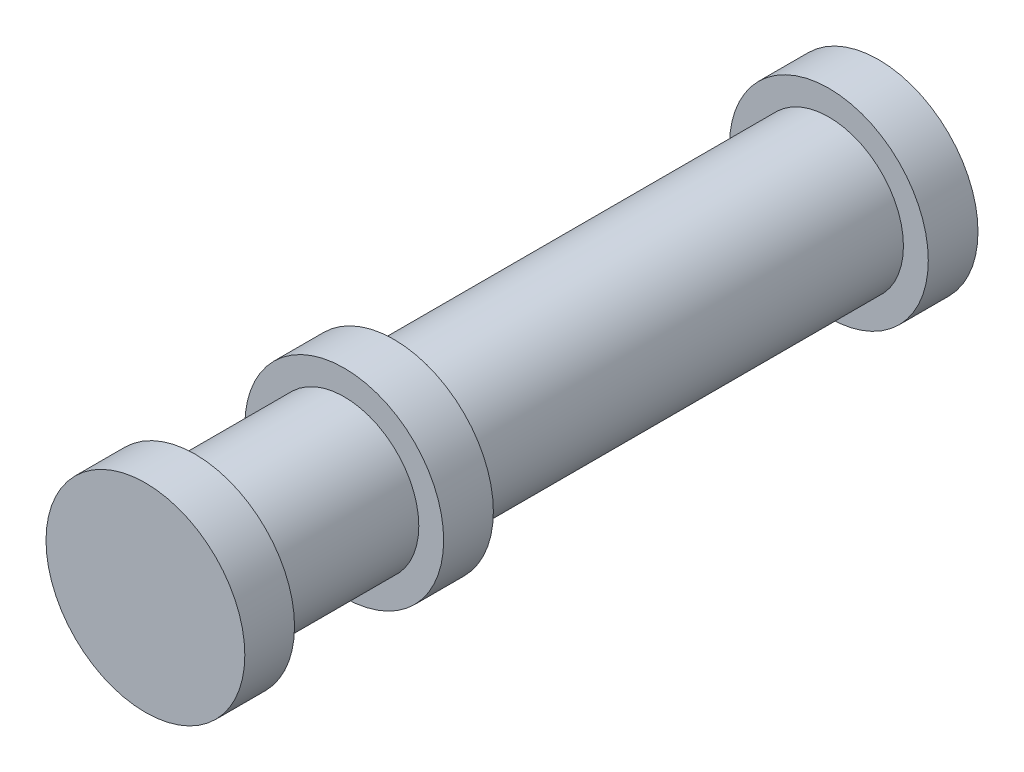
SolidWorks part; units mm, degrees
ref_plane "前视基准面" through (0, 0, 0) normal (0, 0, 1) x (1, 0, 0)
ref_plane "上视基准面" through (0, 0, 0) normal (0, 1, 0) x (1, 0, 0)
ref_plane "右视基准面" through (0, 0, 0) normal (1, 0, 0) x (0, 0, -1)
other "Configuration Table"
sketch "草图1" plane through (0, 0, 0) normal (0, 0, 1) x (1, 0, 0)
  line L0 (0, 0) -> (50000, 0) construction
  line L1 (0, 0) -> (0, 50000) construction
  circle A0 centre (0, 0) radius 3
extrude "凸台-拉伸1" add sketch "草图1" along normal blind 17.5 contours A0
sketch "草图2" plane through (0, 0, 0) normal (0, 0, -1) x (-1, 0, 0)
  circle A0 centre (0, 0) radius 4
extrude "凸台-拉伸2" add sketch "草图2" along normal blind 2
sketch "草图3" plane through (0, 0, 17.5) normal (0, 0, 1) x (1, 0, 0)
  circle A0 centre (0, 0) radius 4
extrude "凸台-拉伸3" add sketch "草图3" along normal blind 2
sketch "草图4" plane through (0, 0, 19.5) normal (0, 0, 1) x (1, 0, 0)
  circle A0 centre (0, 0) radius 3
extrude "凸台-拉伸4" add sketch "草图4" along normal blind 20
sketch "草图5" plane through (0, 0, 39.5) normal (0, 0, 1) x (1, 0, 0)
  circle A0 centre (0, 0) radius 4
extrude "凸台-拉伸5" add sketch "草图5" along normal blind 2
sketch "草图7" plane through (0, 0, 41.5) normal (0, 0, 1) x (1, 0, 0)
  circle A0 centre (0, 0) radius 4
extrude "切除-拉伸1" cut sketch "草图7" against normal blind 16
sketch "草图8" plane through (0, 0, 25.5) normal (0, 0, 1) x (1, 0, 0)
  circle A0 centre (0, 0) radius 4
extrude "凸台-拉伸6" add sketch "草图8" along normal blind 2
